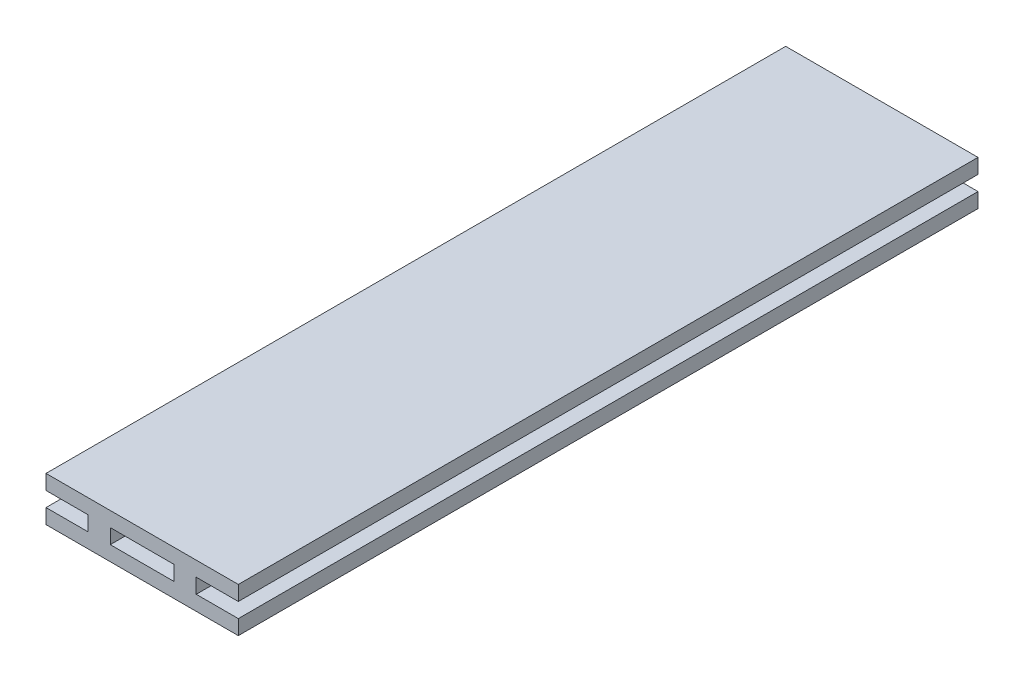
SolidWorks part; units mm, degrees
ref_plane "Front Plane" through (0, 0, 0) normal (0, 0, 1) x (1, 0, 0)
ref_plane "Top Plane" through (0, 0, 0) normal (0, 1, 0) x (1, 0, 0)
ref_plane "Right Plane" through (0, 0, 0) normal (1, 0, 0) x (0, 0, -1)
sketch "Sketch2" plane through (0, 0, 0) normal (0, 0, 1) x (1, 0, 0)
  line L0 (0, 3) -> (0, -3) construction
  line L1 (-13, 3) -> (13, 3)
  line L2 (-13, 3) -> (-13, -3)
  line L3 (-13, -3) -> (13, -3)
  line L4 (13, 3) -> (13, -3)
  line L5 (-13, 3) -> (13, -3) construction
  line L6 (-13, -3) -> (13, 3) construction
  line L7 (-18.6888, 1) -> (-7.3112, 1)
  line L8 (-18.6888, 1) -> (-18.6888, -1)
  line L9 (-18.6888, -1) -> (-7.3112, -1)
  line L10 (-7.3112, 1) -> (-7.3112, -1)
  line L11 (-18.6888, 1) -> (-7.3112, -1) construction
  line L12 (-18.6888, -1) -> (-7.3112, 1) construction
  line L13 (-4.3112, 1) -> (4.3112, 1)
  line L14 (-4.3112, 1) -> (-4.3112, -1)
  line L15 (-4.3112, -1) -> (4.3112, -1)
  line L16 (4.3112, 1) -> (4.3112, -1)
  line L17 (-4.3112, 1) -> (4.3112, -1) construction
  line L18 (-4.3112, -1) -> (4.3112, 1) construction
  line L19 (18.6888, -1) -> (7.3112, -1)
  line L20 (7.3112, 1) -> (7.3112, -1)
  line L21 (18.6888, 1) -> (7.3112, 1)
  line L22 (18.6888, 1) -> (18.6888, -1)
  point P0 (0, 0)
  point P6 (-13, 0)
  point P11 (0, 0)
  dimension "D1" = 6
  dimension "D2" = 2
  dimension "D3" = 2
  dimension "D4" = 3
  dimension "D5" = 26
extrude "Boss-Extrude1" add sketch "Sketch2" along normal blind 100 contours L21 L4 L1 L2 L7 L10 L9 L3 L19 L20 L13 L16 L15 L14
